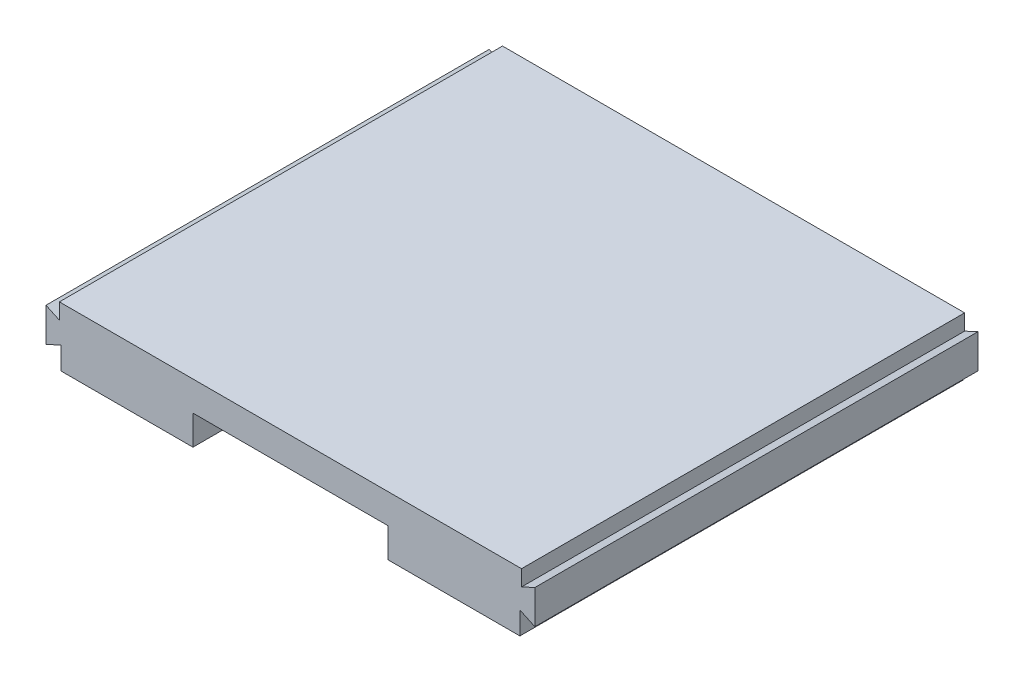
SolidWorks part; units mm, degrees
ref_plane "Front Plane" through (0, 0, 0) normal (0, 0, 1) x (1, 0, 0)
ref_plane "Top Plane" through (0, 0, 0) normal (0, 1, 0) x (1, 0, 0)
ref_plane "Right Plane" through (0, 0, 0) normal (1, 0, 0) x (0, 0, -1)
sketch "Sketch1" plane through (0, 0, 0) normal (0, 1, 0) x (1, 0, 0)
  line L0 (0, -55) -> (0, 55) construction
  line L5 (-19.55, 49) -> (-16.55, 49)
  line L6 (-19.55, 49) -> (-19.55, 0)
  line L7 (-19.55, 0) -> (-16.55, 0)
  line L8 (-16.55, 49) -> (-16.55, 0)
  line L9 (16.55, 49) -> (16.55, 0)
  line L10 (19.55, 0) -> (16.55, 0)
  line L11 (19.55, 49) -> (19.55, 0)
  line L12 (19.55, 49) -> (16.55, 49)
  dimension "D1" = 33.1
  dimension "D2" = 3
  dimension "D3" = 49
extrude "Boss-Extrude1" add sketch "Sketch1" along normal blind 10
sketch "Sketch2" plane through (0, 10, 0) normal (0, 1, 0) x (1, 0, 0)
  line L0 (16.55, 49) -> (16.55, 0) construction
  line L1 (-16.55, 49) -> (16.55, 49)
  line L2 (-16.55, 49) -> (-16.55, 19)
  line L3 (-16.55, 19) -> (16.55, 19)
  line L4 (16.55, 49) -> (16.55, 19)
  dimension "D1" = 30
extrude "Boss-Extrude2" add sketch "Sketch2" along normal blind 4 from surface at -10 starting at face at (18.05, 0, -24.5)
sketch "Sketch3" plane through (0, 10, 0) normal (0, 1, 0) x (1, 0, 0)
  line L0 (-16.55, 49) -> (-19.55, 49) construction
  line L1 (-6.6, 49) -> (6.6, 49)
  line L2 (-6.6, 49) -> (-6.6, 19)
  line L3 (-6.6, 19) -> (6.6, 19)
  line L4 (6.6, 49) -> (6.6, 19)
  line L5 (-16.55, 19) -> (16.55, 19) construction
  point P8 (0, 19)
  dimension "D1" = 13.2
extrude "Cut-Extrude1" cut sketch "Sketch3" along normal blind 2 from surface at -10 starting at face at (0, 0, -17)
sketch "Sketch5" plane through (-19.55, 0, 0) normal (-1, 0, 0) x (0, 0, 1)
  line L36 (-49, 10) -> (0, 10) construction
  line L37 (0, 10) -> (0, 0) construction
  line B0 (-4.75, 7.2361) -> (-4.8548, 6.8247)
  line B1 (-5.1452, 6.8247) -> (-5.25, 7.2361)
  line B2 (-4.5123, 6.7643) -> (-4.4701, 7.1867)
  line B3 (-4.0003, 7.0157) -> (-4.2395, 6.665)
  line B4 (-3.9383, 6.4911) -> (-3.7542, 6.8736)
  line B5 (-3.3712, 6.5522) -> (-3.7159, 6.3045)
  line B6 (-3.4924, 6.0381) -> (-3.1885, 6.3345)
  line B7 (-2.9385, 5.9015) -> (-3.3472, 5.7866)
  line B8 (-3.2283, 5.4598) -> (-2.8413, 5.6345)
  line B9 (-2.7545, 5.1421) -> (-3.1778, 5.1739)
  line B10 (-3.1778, 4.8261) -> (-2.7545, 4.8579)
  line B11 (-2.8413, 4.3655) -> (-3.2283, 4.5402)
  line B12 (-3.3472, 4.2134) -> (-2.9385, 4.0985)
  line B13 (-3.1885, 3.6655) -> (-3.4924, 3.9619)
  line B14 (-3.7159, 3.6955) -> (-3.3712, 3.4478)
  line B15 (-3.7542, 3.1264) -> (-3.9383, 3.5089)
  line B16 (-4.2395, 3.335) -> (-4.0003, 2.9843)
  line B17 (-4.4701, 2.8133) -> (-4.5123, 3.2357)
  line B18 (-4.8548, 3.1753) -> (-4.75, 2.7639)
  line B19 (-5.25, 2.7639) -> (-5.1452, 3.1753)
  line B20 (-5.4877, 3.2357) -> (-5.5299, 2.8133)
  line B21 (-5.9997, 2.9843) -> (-5.7605, 3.335)
  line B22 (-6.0617, 3.5089) -> (-6.2458, 3.1264)
  line B23 (-6.6288, 3.4478) -> (-6.2841, 3.6955)
  line B24 (-6.5076, 3.9619) -> (-6.8115, 3.6655)
  line B25 (-7.0615, 4.0985) -> (-6.6528, 4.2134)
  line B26 (-6.7717, 4.5402) -> (-7.1587, 4.3655)
  line B27 (-7.2455, 4.8579) -> (-6.8222, 4.8261)
  line B28 (-6.8222, 5.1739) -> (-7.2455, 5.1421)
  line B29 (-7.1587, 5.6345) -> (-6.7717, 5.4598)
  line B30 (-6.6528, 5.7866) -> (-7.0615, 5.9015)
  line B31 (-6.8115, 6.3345) -> (-6.5076, 6.0381)
  line B32 (-6.2841, 6.3045) -> (-6.6288, 6.5522)
  line B33 (-6.2458, 6.8736) -> (-6.0617, 6.4911)
  line B34 (-5.7605, 6.665) -> (-5.9997, 7.0157)
  line B35 (-5.5299, 7.1867) -> (-5.4877, 6.7643)
  arc B36 (-5.9997, 7.0157) -> (-6.2458, 6.8736) centre (-5, 5) ccw
  arc B37 (-5.5554, 6.6595) -> (-5.6412, 6.6283) centre (-5, 5) ccw
  arc B38 (-4.9543, 6.7494) -> (-4.8548, 6.8247) centre (-4.9517, 6.8494) ccw
  arc B39 (-5.0457, 6.7494) -> (-5.1452, 6.8247) centre (-5.0483, 6.8494) cw
  arc B40 (-4.4446, 6.6595) -> (-4.5123, 6.7643) centre (-4.4128, 6.7543) cw
  arc B41 (-4.3588, 6.6283) -> (-4.2395, 6.665) centre (-4.3221, 6.7213) ccw
  arc B42 (-3.9105, 6.3695) -> (-3.9383, 6.4911) centre (-3.8482, 6.4477) cw
  arc B43 (-3.8405, 6.3108) -> (-3.7159, 6.3045) centre (-3.7743, 6.3857) ccw
  arc B44 (-3.5078, 5.9142) -> (-3.4924, 6.0381) centre (-3.4225, 5.9665) cw
  arc B45 (-3.4621, 5.8352) -> (-3.3472, 5.7866) centre (-3.3743, 5.8829) ccw
  arc B46 (-3.2851, 5.3487) -> (-3.2283, 5.4598) centre (-3.1871, 5.3687) cw
  arc B47 (-3.2692, 5.2588) -> (-3.1778, 5.1739) centre (-3.1703, 5.2736) ccw
  arc B48 (-3.2692, 4.7412) -> (-3.1778, 4.8261) centre (-3.1703, 4.7264) cw
  arc B49 (-3.2851, 4.6513) -> (-3.2283, 4.5402) centre (-3.1871, 4.6313) ccw
  arc B50 (-3.4621, 4.1648) -> (-3.3472, 4.2134) centre (-3.3743, 4.1171) cw
  arc B51 (-3.5078, 4.0858) -> (-3.4924, 3.9619) centre (-3.4225, 4.0335) ccw
  arc B52 (-3.8405, 3.6892) -> (-3.7159, 3.6955) centre (-3.7743, 3.6143) cw
  arc B53 (-3.9105, 3.6305) -> (-3.9383, 3.5089) centre (-3.8482, 3.5523) ccw
  arc B54 (-4.3588, 3.3717) -> (-4.2395, 3.335) centre (-4.3221, 3.2787) cw
  arc B55 (-4.4446, 3.3405) -> (-4.5123, 3.2357) centre (-4.4128, 3.2457) ccw
  arc B56 (-4.9543, 3.2506) -> (-4.8548, 3.1753) centre (-4.9517, 3.1506) cw
  arc B57 (-5.0457, 3.2506) -> (-5.1452, 3.1753) centre (-5.0483, 3.1506) ccw
  arc B58 (-5.5554, 3.3405) -> (-5.4877, 3.2357) centre (-5.5872, 3.2457) cw
  arc B59 (-5.6412, 3.3717) -> (-5.7605, 3.335) centre (-5.6779, 3.2787) ccw
  arc B60 (-6.0895, 3.6305) -> (-6.0617, 3.5089) centre (-6.1518, 3.5523) cw
  arc B61 (-6.1595, 3.6892) -> (-6.2841, 3.6955) centre (-6.2257, 3.6143) ccw
  arc B62 (-6.4922, 4.0858) -> (-6.5076, 3.9619) centre (-6.5775, 4.0335) cw
  arc B63 (-6.5379, 4.1648) -> (-6.6528, 4.2134) centre (-6.6257, 4.1171) ccw
  arc B64 (-6.7149, 4.6513) -> (-6.7717, 4.5402) centre (-6.8129, 4.6313) cw
  arc B65 (-6.7308, 4.7412) -> (-6.8222, 4.8261) centre (-6.8297, 4.7264) ccw
  arc B66 (-6.7308, 5.2588) -> (-6.8222, 5.1739) centre (-6.8297, 5.2736) cw
  arc B67 (-6.7149, 5.3487) -> (-6.7717, 5.4598) centre (-6.8129, 5.3687) ccw
  arc B68 (-6.5379, 5.8352) -> (-6.6528, 5.7866) centre (-6.6257, 5.8829) cw
  arc B69 (-6.4922, 5.9142) -> (-6.5076, 6.0381) centre (-6.5775, 5.9665) ccw
  arc B70 (-6.1595, 6.3108) -> (-6.2841, 6.3045) centre (-6.2257, 6.3857) cw
  arc B71 (-6.0895, 6.3695) -> (-6.0617, 6.4911) centre (-6.1518, 6.4477) ccw
  arc B72 (-5.6412, 6.6283) -> (-5.7605, 6.665) centre (-5.6779, 6.7213) cw
  arc B73 (-5.5554, 6.6595) -> (-5.4877, 6.7643) centre (-5.5872, 6.7543) ccw
  arc B74 (-4.9543, 6.7494) -> (-5.0457, 6.7494) centre (-5, 5) ccw
  arc B75 (-4.3588, 6.6283) -> (-4.4446, 6.6595) centre (-5, 5) ccw
  arc B76 (-3.8405, 6.3108) -> (-3.9105, 6.3695) centre (-5, 5) ccw
  arc B77 (-3.4621, 5.8352) -> (-3.5078, 5.9142) centre (-5, 5) ccw
  arc B78 (-3.2692, 5.2588) -> (-3.2851, 5.3487) centre (-5, 5) ccw
  arc B79 (-6.0895, 6.3695) -> (-6.1595, 6.3108) centre (-5, 5) ccw
  arc B80 (-6.4922, 5.9142) -> (-6.5379, 5.8352) centre (-5, 5) ccw
  arc B81 (-6.7149, 5.3487) -> (-6.7308, 5.2588) centre (-5, 5) ccw
  arc B82 (-6.7308, 4.7412) -> (-6.7149, 4.6513) centre (-5, 5) ccw
  arc B83 (-6.5379, 4.1648) -> (-6.4922, 4.0858) centre (-5, 5) ccw
  arc B84 (-6.1595, 3.6892) -> (-6.0895, 3.6305) centre (-5, 5) ccw
  arc B85 (-5.6412, 3.3717) -> (-5.5554, 3.3405) centre (-5, 5) ccw
  arc B86 (-5.0457, 3.2506) -> (-4.9543, 3.2506) centre (-5, 5) ccw
  arc B87 (-4.4446, 3.3405) -> (-4.3588, 3.3717) centre (-5, 5) ccw
  arc B88 (-3.9105, 3.6305) -> (-3.8405, 3.6892) centre (-5, 5) ccw
  arc B89 (-3.2851, 4.6513) -> (-3.2692, 4.7412) centre (-5, 5) ccw
  arc B90 (-5.25, 7.2361) -> (-5.5299, 7.1867) centre (-5, 5) ccw
  arc B91 (-4.4701, 7.1867) -> (-4.75, 7.2361) centre (-5, 5) ccw
  arc B92 (-3.7542, 6.8736) -> (-4.0003, 7.0157) centre (-5, 5) ccw
  arc B93 (-3.1885, 6.3345) -> (-3.3712, 6.5522) centre (-5, 5) ccw
  arc B94 (-2.8413, 5.6345) -> (-2.9385, 5.9015) centre (-5, 5) ccw
  arc B95 (-2.7545, 4.8579) -> (-2.7545, 5.1421) centre (-5, 5) ccw
  arc B96 (-2.9385, 4.0985) -> (-2.8413, 4.3655) centre (-5, 5) ccw
  arc B97 (-3.3712, 3.4478) -> (-3.1885, 3.6655) centre (-5, 5) ccw
  arc B98 (-4.0003, 2.9843) -> (-3.7542, 3.1264) centre (-5, 5) ccw
  arc B99 (-4.75, 2.7639) -> (-4.4701, 2.8133) centre (-5, 5) ccw
  arc B100 (-5.5299, 2.8133) -> (-5.25, 2.7639) centre (-5, 5) ccw
  arc B101 (-6.2458, 3.1264) -> (-5.9997, 2.9843) centre (-5, 5) ccw
  arc B102 (-6.8115, 3.6655) -> (-6.6288, 3.4478) centre (-5, 5) ccw
  arc B103 (-7.1587, 4.3655) -> (-7.0615, 4.0985) centre (-5, 5) ccw
  arc B104 (-7.2455, 5.1421) -> (-7.2455, 4.8579) centre (-5, 5) ccw
  arc B105 (-7.0615, 5.9015) -> (-7.1587, 5.6345) centre (-5, 5) ccw
  arc B106 (-6.6288, 6.5522) -> (-6.8115, 6.3345) centre (-5, 5) ccw
  arc B107 (-3.5078, 4.0858) -> (-3.4621, 4.1648) centre (-5, 5) ccw
  dimension "D1" = 5
  dimension "D2" = 5
sketch_block_instance "Block1-1"
sketch_block "Block1" parameters "D1"=0.1, "D2"=0.5
extrude "Cut-Extrude2" cut sketch "Sketch5" along normal blind 2.5 from surface at -3 starting at face at (-16.55, 4.6667, -22.6667)
sketch "Sketch6" plane through (-19.55, 0, 0) normal (-1, 0, 0) x (0, 0, 1)
  line L0 (-49, 10) -> (0, 10) construction
  line L1 (0, 10) -> (0, 0) construction
  circle A0 centre (-5, 5) radius 1.6
  dimension "D3" = 3.2
  dimension "D1" = 5
  dimension "D2" = 5
extrude "Cut-Extrude3" cut sketch "Sketch6" against normal blind 2.5 from surface at -36.1 starting at face at (16.55, 4.6667, -22.6667)
sketch "Sketch9" plane through (0, 10, 0) normal (0, 1, 0) x (1, 0, 0)
  line L1 (16.55, 19) -> (16.55, 0) construction
  line L3 (16.55, 0) -> (19.55, 0) construction
  line L5 (16.55, 5) -> (17.55, 5)
  line L6 (17.55, 5) -> (19.05, 0)
  line L7 (16.55, 5) -> (16.55, 0)
  line L8 (16.55, 0) -> (19.05, 0)
  dimension "D1" = 5
  dimension "D2" = 2.5
  dimension "D3" = 1
extrude "Cut-Extrude4" cut sketch "Sketch9" against normal blind 3.2 from offset 3.4 offset against normal yes
sketch "Sketch10" plane through (0, 0, -49) normal (0, 0, -1) x (-1, 0, 0)
  line L0 (-15.6441, 2.9276) -> (-16.55, 3.35)
  line L1 (-16.55, 3.35) -> (-16.55, 1.05)
  line L2 (-16.55, 1.05) -> (-15.5349, 1.5234)
  line L3 (-19.55, 0) -> (-6.6, 0) construction
  line L7 (-19.9628, 10.8743) -> (-19.9628, -2.3478)
  line L8 (-19.9628, -2.3478) -> (-15.5349, -2.3478)
  line L9 (-15.5349, -2.3478) -> (-15.5349, 1.5234)
  line L11 (-16.55, 10) -> (-16.55, 4) construction
  line L12 (-19.9628, 10.8743) -> (-15.6441, 10.8743)
  line L13 (-15.6441, 10.8743) -> (-15.6441, 2.9276)
  line L14 (0, 7.2721) -> (0, -7.2721) construction
  line L15 (19.9628, 10.8743) -> (15.6441, 10.8743)
  line L16 (19.9628, 10.8743) -> (19.9628, -2.3478)
  line L17 (19.9628, -2.3478) -> (15.5349, -2.3478)
  line L18 (15.5349, -2.3478) -> (15.5349, 1.5234)
  line L19 (16.55, 1.05) -> (15.5349, 1.5234)
  line L20 (16.55, 3.35) -> (16.55, 1.05)
  line L21 (15.6441, 2.9276) -> (16.55, 3.35)
  line L22 (15.6441, 10.8743) -> (15.6441, 2.9276)
  point P2 (-16.55, 2.2)
  dimension "D1" = 2.2
  dimension "D2" = 65
  dimension "D3" = 65
  dimension "D4" = 2.3
extrude "Cut-Extrude6" cut sketch "Sketch10" against normal through all
